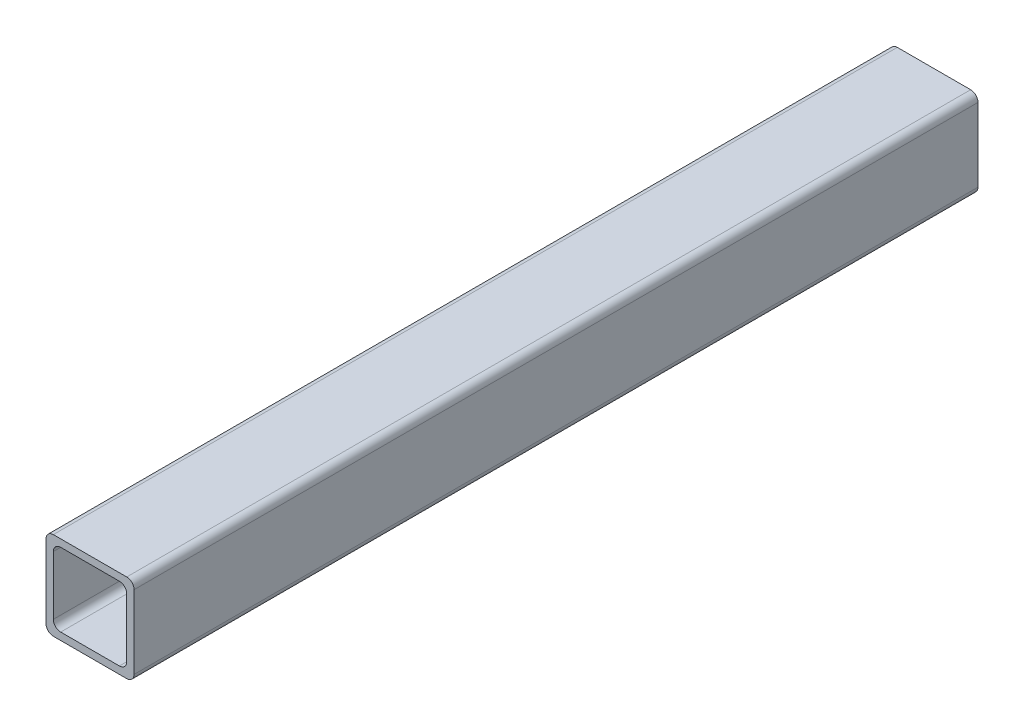
SolidWorks part; units mm, degrees
ref_plane "Front Plane" through (0, 0, 0) normal (0, 0, 1) x (1, 0, 0)
ref_plane "Top Plane" through (0, 0, 0) normal (0, 1, 0) x (1, 0, 0)
ref_plane "Right Plane" through (0, 0, 0) normal (1, 0, 0) x (0, 0, -1)
sketch "Sketch1" plane through (0, 0, 0) normal (0, 0, 1) x (1, 0, 0)
  line L1 (-50, -60) -> (50, -60)
  line L2 (-60, -50) -> (-60, 50)
  line L3 (-50, 60) -> (50, 60)
  line L4 (60, -50) -> (60, 50)
  line L5 (-60, -60) -> (60, 60) construction
  line L6 (-60, 60) -> (60, -60) construction
  line L7 (-40, -50) -> (40, -50)
  line L8 (-50, -40) -> (-50, 40)
  line L9 (-40, 50) -> (40, 50)
  line L10 (50, -40) -> (50, 40)
  line L11 (-50, -50) -> (50, 50) construction
  line L12 (-50, 50) -> (50, -50) construction
  arc A0 (50, -60) -> (60, -50) centre (50, -50) ccw
  arc A1 (50, 60) -> (60, 50) centre (50, 50) cw
  arc A2 (-60, 50) -> (-50, 60) centre (-50, 50) cw
  arc A3 (-50, -60) -> (-60, -50) centre (-50, -50) cw
  arc A4 (-40, -50) -> (-50, -40) centre (-40, -40) cw
  arc A5 (40, -50) -> (50, -40) centre (40, -40) ccw
  arc A6 (40, 50) -> (50, 40) centre (40, 40) cw
  arc A7 (-50, 40) -> (-40, 50) centre (-40, 40) cw
  point P0 (0, 0)
  point P6 (0, 0)
  dimension "D4" = 10
  dimension "D1" = 120
  dimension "D2" = 120
  dimension "D3" = 100
extrude "Boss-Extrude1" add sketch "Sketch1" along normal mid plane 1150
sketch "Sketch2" plane through (0, -60, 0) normal (0, -1, 0) x (1, 0, 0)
  line L0 (0, 0) -> (60, 0) construction
  line L1 (60, 575) -> (60, -575) construction
  line L2 (60, 0) -> (-60, 0) construction
  line L3 (-60, 575) -> (-60, -575) construction
  circle A0 centre (0, 501) radius 8.5
  circle A1 centre (0, -501) radius 8.5
  dimension "D1" = 17
  dimension "D2" = 501
  dimension "D3" = 60
extrude "Cut-Extrude1" cut sketch "Sketch2" against normal blind 10
